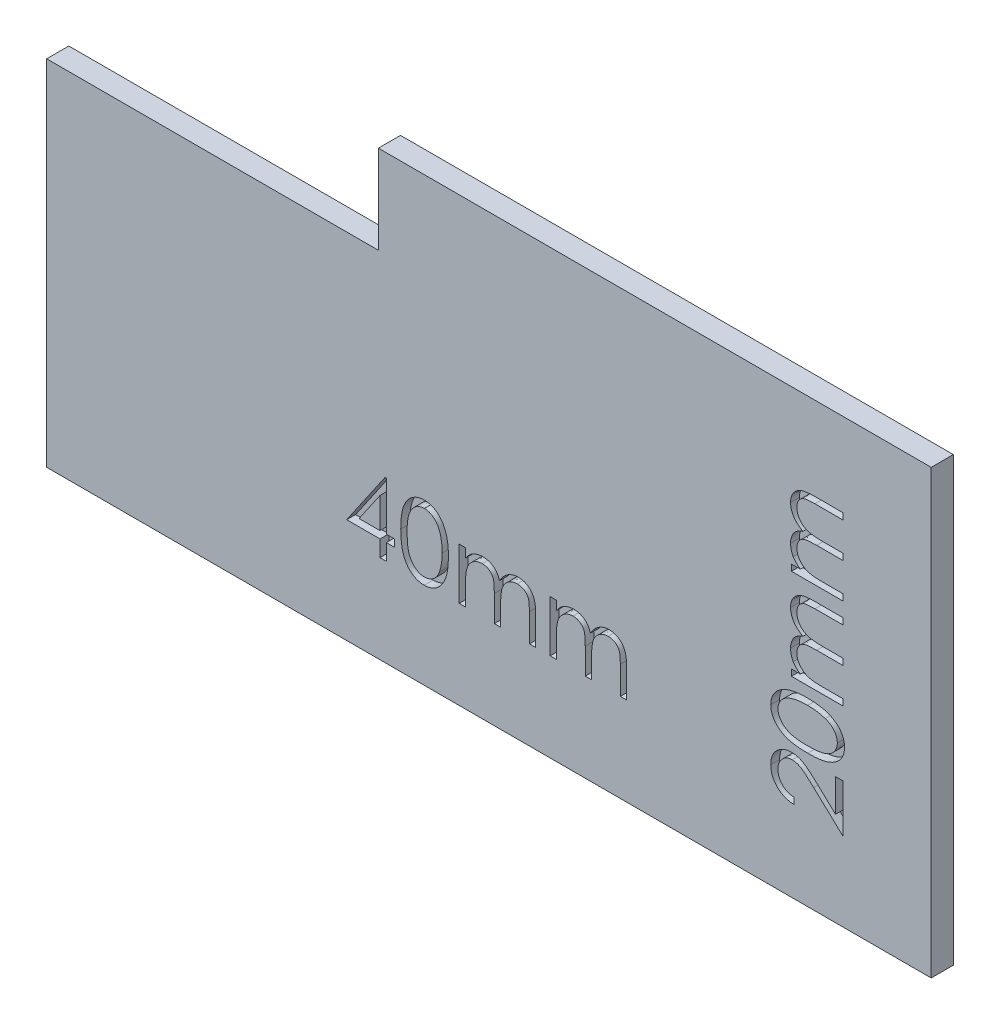
SolidWorks part; units mm, degrees
ref_plane "Front Plane" through (0, 0, 0) normal (0, 0, 1) x (1, 0, 0)
ref_plane "Top Plane" through (0, 0, 0) normal (0, 1, 0) x (1, 0, 0)
ref_plane "Right Plane" through (0, 0, 0) normal (1, 0, 0) x (0, 0, -1)
sketch "Sketch1" plane through (0, 0, 0) normal (0, 0, 1) x (1, 0, 0)
  line L1 (0, 0) -> (40, 0)
  line L2 (0, 0) -> (0, 20)
  line L3 (0, 20) -> (40, 20)
  line L4 (40, 0) -> (40, 20)
  dimension "D1" = 40
  dimension "D2" = 20
extrude "Boss-Extrude1" add sketch "Sketch1" along normal blind 1
sketch "Sketch2" plane through (0, 0, 1) normal (0, 0, 1) x (1, 0, 0)
  line L0 (0, 4) -> (40, 4) construction
  line L1 (0, 20) -> (0, 0) construction
  line L2 (40, 0) -> (40, 20) construction
  line L3 (36, 20) -> (36, 0) construction
  line L4 (40, 20) -> (0, 20) construction
  line L5 (0, 0) -> (40, 0) construction
  line L6 (0, 4) -> (8, 4) construction
  text T0 "40mm"
  text T1 "20mm"
  dimension "D1" = 4
  dimension "D2" = 4
  dimension "D3" = 8
sketch "Sketch3" plane through (0, 0, 1) normal (0, 0, 1) x (1, 0, 0)
  line L0 (0, 20) -> (0, 0) construction
  line L1 (0, 20) -> (15, 20)
  line L2 (0, 20) -> (0, 16)
  line L3 (0, 16) -> (15, 16)
  line L4 (15, 20) -> (15, 16)
  line L5 (40, 20) -> (0, 20) construction
  line L6 (0, 16) -> (40, 16) construction
  line L7 (40, 0) -> (40, 20) construction
  dimension "D3" = 15
  dimension "D4" = 4
extrude "Cut-Extrude1" cut sketch "Sketch3" against normal up to next
extrude "Cut-Extrude2" cut sketch "Sketch2" against normal blind 0.4
